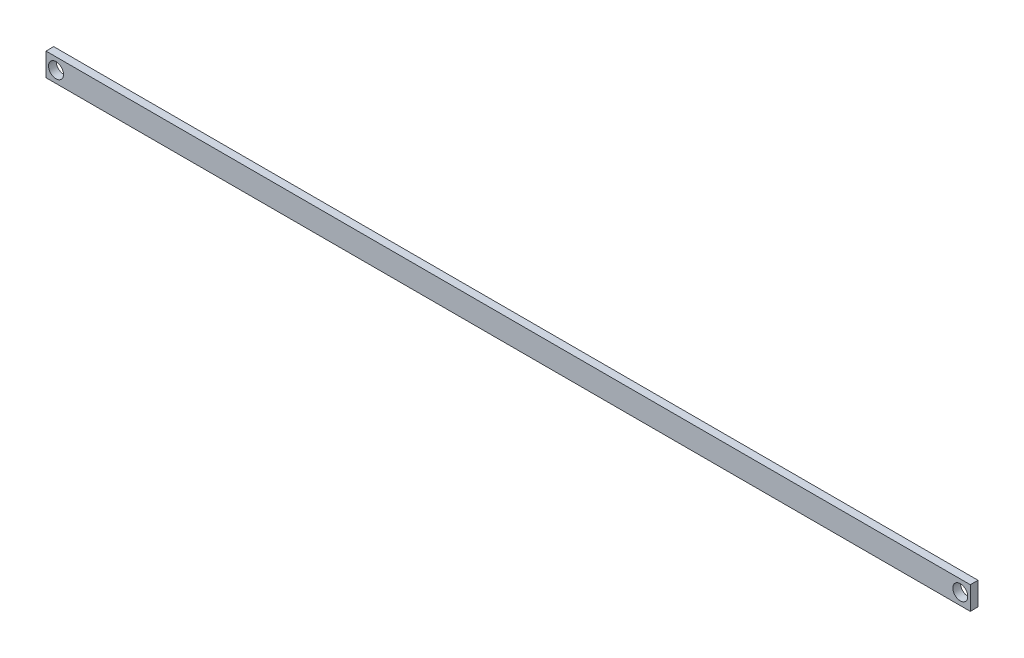
SolidWorks part; units mm, degrees
material "Plain Carbon Steel"
ref_plane "Front Plane" through (0, 0, 0) normal (0, 0, 1) x (1, 0, 0)
ref_plane "Top Plane" through (0, 0, 0) normal (0, 1, 0) x (1, 0, 0)
ref_plane "Right Plane" through (0, 0, 0) normal (1, 0, 0) x (0, 0, -1)
sketch "Sketch1" plane through (0, 0, 0) normal (0, 0, 1) x (1, 0, 0)
  line L0 (0, 0) -> (600, 0)
  line L1 (0, 0) -> (0, -15)
  line L2 (0, -15) -> (600, -15)
  line L3 (600, -15) -> (600, 0)
  circle A1 centre (6.5, -7.5) radius 4.85
  circle A2 centre (593.5, -7.5) radius 4.85
  point P9 (600, -7.5)
  dimension "D3" = 9.7
  dimension "D5" = 9.7
  dimension "D1" = 600
  dimension "D2" = 15
  dimension "D4" = 6.5
  dimension "D6" = 6.5
extrude "Boss-Extrude1" add sketch "Sketch1" against normal blind 5
